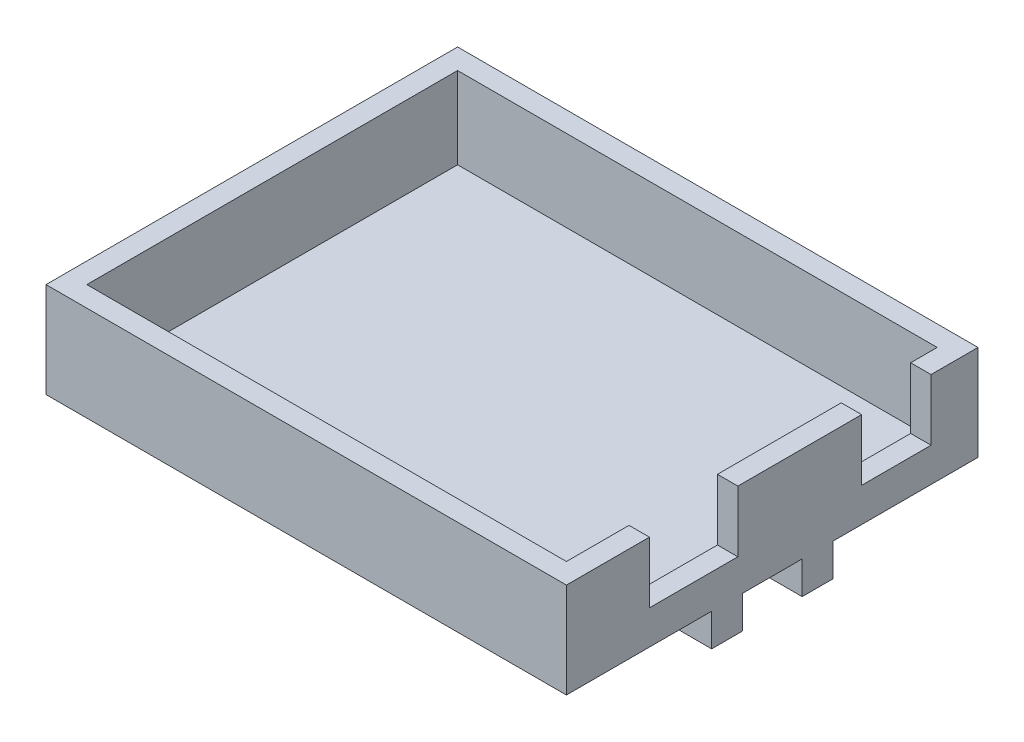
SolidWorks part; units mm, degrees
ref_plane "Front Plane" through (0, 0, 0) normal (0, 0, 1) x (1, 0, 0)
ref_plane "Top Plane" through (0, 0, 0) normal (0, 1, 0) x (1, 0, 0)
ref_plane "Right Plane" through (0, 0, 0) normal (1, 0, 0) x (0, 0, -1)
sketch "Sketch1" plane through (0, 0, 0) normal (0, 1, 0) x (1, 0, 0)
  line L1 (-38.25, -30.25) -> (38.25, -30.25)
  line L2 (-38.25, -30.25) -> (-38.25, 30.25)
  line L3 (-38.25, 30.25) -> (38.25, 30.25)
  line L4 (38.25, -30.25) -> (38.25, 30.25)
  line L5 (-38.25, -30.25) -> (38.25, 30.25) construction
  line L6 (-38.25, 30.25) -> (38.25, -30.25) construction
  point P0 (0, 0)
  dimension "D1" = 76.5
  dimension "D2" = 60.5
extrude "Boss-Extrude1" add sketch "Sketch1" along normal blind 14
sketch "Sketch2" plane through (0, 14, 0) normal (0, 1, 0) x (1, 0, 0)
  line L5 (-35.25, 27.25) -> (35.25, 27.25)
  line L6 (-35.25, 27.25) -> (-35.25, -27.25)
  line L7 (-35.25, -27.25) -> (35.25, -27.25)
  line L8 (35.25, 27.25) -> (35.25, -27.25)
  line L9 (-35.25, 27.25) -> (35.25, -27.25) construction
  line L10 (-35.25, -27.25) -> (35.25, 27.25) construction
  point P0 (0, 0)
  dimension "D1" = 70.5
  dimension "60" = 54.5
extrude "Cut-Extrude1" cut sketch "Sketch2" against normal blind 12
sketch "Sketch4" plane through (38.25, 0, 0) normal (1, 0, 0) x (0, 0, -1)
  line L0 (30.25, 5) -> (27.25, 5) construction
  line L1 (-30.25, 14) -> (-30.25, 0) construction
  line L2 (-18.05, 14) -> (-18.05, 5)
  line L7 (-30.25, 14) -> (30.25, 14) construction
  line L8 (-18.05, 5) -> (-5.05, 5)
  line L9 (-18.05, 14) -> (-5.05, 14)
  line L10 (-5.05, 14) -> (-5.05, 5)
  line L13 (-5.05, 5) -> (13.15, 5) construction
  line L14 (23.35, 14) -> (13.15, 14)
  line L15 (23.35, 14) -> (23.35, 5)
  line L16 (23.35, 5) -> (13.15, 5)
  line L17 (13.15, 14) -> (13.15, 5)
  line L21 (-30.25, 5) -> (-27.25, 5) construction
  line L22 (-27.25, 5) -> (-18.05, 5) construction
  line L23 (30.25, 14) -> (30.25, 0) construction
  line L24 (27.25, 5) -> (23.35, 5) construction
  dimension "D1" = 13
  dimension "D2" = 9
  dimension "D3" = 10.2
  dimension "D4" = 3
  dimension "D5" = 3
  dimension "D6" = 18.2
  dimension "D7" = 9.2
  dimension "D8" = 3.9
extrude "Cut-Extrude2" cut sketch "Sketch4" against normal up to next
sketch "Sketch5" plane through (0, 0, 0) normal (0, -1, 0) x (1, 0, 0)
  line L0 (0, -4.45) -> (0, 4.45) construction
  line L1 (-38.25, -30.25) -> (-38.25, 30.25) construction
  line L2 (-38.25, 4.4) -> (38.25, 4.4)
  line L3 (-38.25, 4.4) -> (-38.25, 8.9)
  line L4 (-38.25, 8.9) -> (38.25, 8.9)
  line L5 (38.25, 4.4) -> (38.25, 8.9)
  line L6 (38.25, 30.25) -> (38.25, -30.25) construction
  point P4 (0, 0)
  dimension "D1" = 4.5
  dimension "D2" = 8.9
extrude "Boss-Extrude3" add sketch "Sketch5" along normal blind 4.8
mirror "Mirror1" about plane through (0, 0, 0) normal (0, 0, 1) of "Boss-Extrude3"
